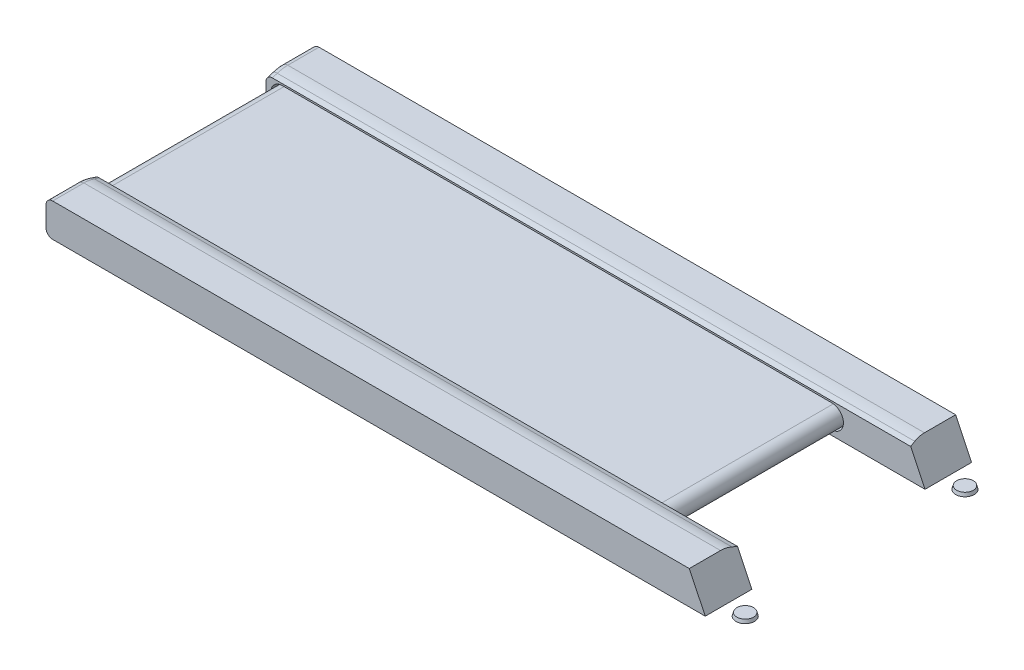
SolidWorks part; units mm, degrees
ref_plane "Front Plane" through (0, 0, 0) normal (0, 0, 1) x (1, 0, 0)
ref_plane "Top Plane" through (0, 0, 0) normal (0, 1, 0) x (1, 0, 0)
ref_plane "Right Plane" through (0, 0, 0) normal (1, 0, 0) x (0, 0, -1)
sketch "Sketch1" plane through (0, 0, 0) normal (0, 1, 0) x (1, 0, 0)
  line L0 (340, -420) -> (340, 420) construction
  line L1 (-1040, 420) -> (1040, 420) construction
  line L2 (-1040, 420) -> (-1040, -420) construction
  line L3 (-1040, -420) -> (1040, -420) construction
  line L4 (1040, 420) -> (1040, -420) construction
  line L5 (-1040, 420) -> (1040, -420) construction
  line L6 (-1040, -420) -> (1040, 420) construction
  point P0 (0, 0)
  dimension "D1" = 2080
  dimension "D2" = 840
  dimension "D3" = 700
ref_plane "Plane1" through (0, 0, 400) normal (0, 0, 1) x (1, 0, 0)
sketch "Sketch2" plane through (0, 0, 400) normal (0, 0, 1) x (1, 0, 0)
  line L0 (-1040, 0) -> (1040, 0) construction
  line L1 (-1040, 0) -> (940, 0)
  line L2 (-1040, 0) -> (-1040, 100)
  line L3 (-1040, 100) -> (892, 100)
  line L5 (-1040, 0) -> (1040, 0) construction
  line L6 (340, 0) -> (340, 1500) construction
  line L7 (940, 0) -> (340, 1250) construction
  line L8 (940, 0) -> (892, 100)
  dimension "D1" = 100
  dimension "D2" = 1500
  dimension "D3" = 250
  dimension "D4" = 100
extrude "Boss-Extrude1" add sketch "Sketch2" against normal blind 140
chamfer "Chamfer1" distance 10 distance2 30 1 edges at (-74, 100, 260)
fillet "Fillet1" radius 100 1 edges at (-74, 100, 290)
fillet "Fillet2" radius 20 4 edges at (-1040, 0, 330) (-1040, 92.4342, 267.3025) (-1040, 98.7087, 290.2095) (-1040, 100, 353.1139)
mirror "Mirror2" about plane through (0, 0, 0) normal (0, 0, 1) of bodies 218
sketch "Sketch12" plane through (0, 0, 0) normal (0, 0, 1) x (1, 0, 0)
  line L0 (-1040, 50) -> (916, 50) construction
  line L1 (-1040, 68.9181) -> (-1040, 20) construction
  line L3 (-990, 50) -> (660, 50) construction
  line L4 (-990, 85) -> (660, 85)
  line L5 (-990, 15) -> (660, 15)
  line L6 (-1040, 80) -> (-1040, 20) construction
  line L7 (940, 0) -> (892, 100) construction
  arc A0 (-990, 85) -> (-990, 15) centre (-990, 50) ccw
  arc A1 (660, 15) -> (660, 85) centre (660, 50) ccw
  point P4 (-1040, 50)
  point P6 (-990, 50)
  point P7 (660, 50)
  point P10 (-165, 50)
  dimension "D1" = 50
  dimension "D2" = 1700
  dimension "D3" = 70
extrude "Cut-Extrude1" cut sketch "Sketch12" against normal offset from surface 20 and the other way offset from surface (380 mm away) 20 up to face at (-382.714, 50, -400) other way up to face at (-382.714, 50, 400)
sketch "Sketch13" plane through (0, 0, -380) normal (0, 0, 1) x (1, 0, 0)
  line L2 (-990, 25) -> (660, 25)
  line L3 (660, 75) -> (-990, 75)
  line L4 (-990, 20) -> (660, 20)
  line L5 (660, 80) -> (-990, 80)
  line L6 (-990, 20) -> (660, 20)
  line L7 (660, 80) -> (-990, 80)
  arc A2 (-990, 75) -> (-990, 25) centre (-990, 50) ccw
  arc A3 (660, 25) -> (660, 75) centre (660, 50) ccw
  arc A4 (-990, 80) -> (-990, 20) centre (-990, 50) ccw
  arc A5 (660, 20) -> (660, 80) centre (660, 50) ccw
  arc A6 (-990, 80) -> (-990, 20) centre (-990, 50) ccw
  arc A7 (660, 20) -> (660, 80) centre (660, 50) ccw
  dimension "D1" = 5
  dimension "D2" = 5
extrude "Boss-Extrude4" add sketch "Sketch13" along normal up to surface (760 mm away) separate body up to face at (-165, 50, 380)
sketch "Sketch31" plane through (0, 0, 0) normal (0, -1, 0) x (1, 0, 0)
  line L0 (-1040, 260) -> (-1040, 400) construction
  line L1 (0, 0) -> (-990, 0) construction
  line L2 (-990, 380) -> (-990, -380) construction
  line L3 (-1020, 400) -> (940, 400) construction
  line L4 (0, 0) -> (0, 260) construction
  line L5 (-1020, 260) -> (940, 260) construction
  circle A0 centre (-990, 330) radius 25
  circle A1 centre (-990, -330) radius 25
  circle A2 centre (990, -330) radius 25
  circle A3 centre (990, 330) radius 25
  dimension "D1" = 50
  dimension "D2" = 50
  dimension "D3" = 70
extrude "Boss-Extrude13" add sketch "Sketch31" along normal blind 10 draft 15 separate body draft outward yes
sketch "Sketch32" plane through (0, 0, 0) normal (0, 1, 0) x (1, 0, 0)
  line L0 (-165, 705.2726) -> (-165, -713.8473) construction
  line L1 (-990, -380) -> (-990, 380) construction
  dimension "D1" = 825
